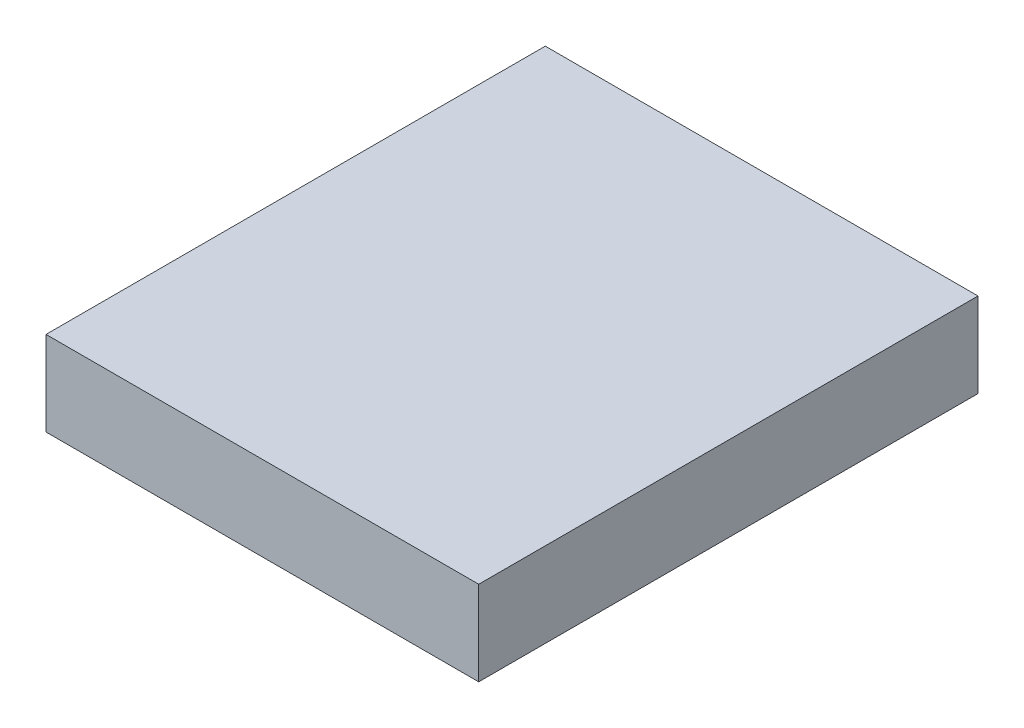
SolidWorks part; units mm, degrees
material "Low Carbon Steel"
ref_plane "Front Plane" through (0, 0, 0) normal (0, 0, 1) x (1, 0, 0)
ref_plane "Top Plane" through (0, 0, 0) normal (0, 1, 0) x (1, 0, 0)
ref_plane "Right Plane" through (0, 0, 0) normal (1, 0, 0) x (0, 0, -1)
sketch "Sketch1" plane through (0, 0, 0) normal (0, 1, 0) x (1, 0, 0)
  line L1 (-65, 0) -> (65, 0)
  line L2 (-65, 0) -> (-65, -150)
  line L3 (-65, -150) -> (65, -150)
  line L4 (65, 0) -> (65, -150)
  dimension "D1" = 130
  dimension "D2" = 150
extrude "Boss-Extrude1" add sketch "Sketch1" along normal blind 25.4
other "Freeze***"
